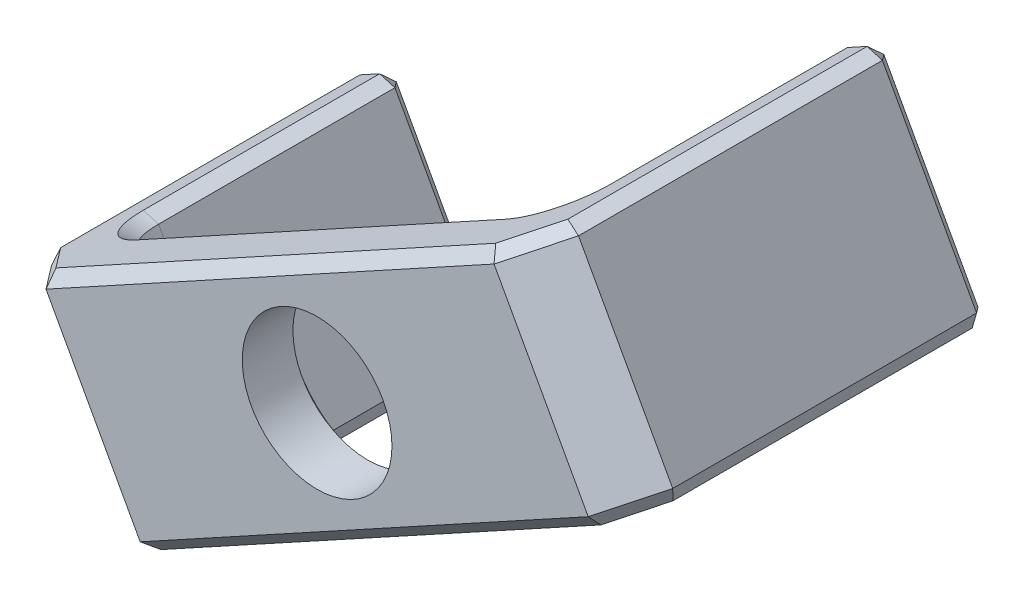
SolidWorks part; units mm, degrees
ref_plane "Front Plane" through (0, 0, 0) normal (0, 0, 1) x (1, 0, 0)
ref_plane "Top Plane" through (0, 0, 0) normal (0, 1, 0) x (1, 0, 0)
ref_plane "Right Plane" through (0, 0, 0) normal (1, 0, 0) x (0, 0, -1)
sketch "Sketch1" plane through (0, 0, 0) normal (0, 0, 1) x (1, 0, 0)
  line L8 (15.2366, 19.4223) -> (24.5673, 2.4136)
  line L10 (-15.2366, -19.4223) -> (-24.5673, -2.4136)
  line L12 (24.129, 2.1731) -> (-14.7982, -19.1818)
  line L14 (-24.129, -2.1731) -> (14.7982, 19.1818)
  line L16 (-14.7982, -19.1818) -> (-15.2366, -19.4223)
  line L17 (-24.129, -2.1731) -> (-24.5673, -2.4136)
  line L18 (14.7982, 19.1818) -> (15.2366, 19.4223)
  line L19 (24.129, 2.1731) -> (24.5673, 2.4136)
  circle A1 centre (0, 0) radius 6.65
extrude "Boss-Extrude1" add sketch "Sketch1" against normal blind 6
sketch "Sketch2" plane through (0, 0, 0) normal (0, 0, 1) x (1, 0, 0)
  line L0 (24.5673, 2.4136) -> (15.2366, 19.4223) construction
  line L1 (-24.5673, -2.4136) -> (-15.2366, -19.4223) construction
  line L2 (24.5673, 2.4136) -> (15.2366, 19.4223)
  line L3 (-24.5673, -2.4136) -> (-15.2366, -19.4223)
  line L4 (-15.2366, -19.4223) -> (-18.7435, -21.3462)
  line L5 (-18.7435, -21.3462) -> (-28.0743, -4.3375)
  line L6 (-28.0743, -4.3375) -> (-24.5673, -2.4136)
  line L7 (24.5673, 2.4136) -> (28.0743, 4.3375)
  line L8 (28.0743, 4.3375) -> (18.7435, 21.3462)
  line L9 (18.7435, 21.3462) -> (15.2366, 19.4223)
extrude "Boss-Extrude2" add sketch "Sketch2" against normal blind 32
fillet "Fillet1" radius 4 2 edges at (-19.902, -10.918, -6) (19.902, 10.918, -6)
chamfer "Chamfer1" distance 4 angle 45 2 edges at (-23.4089, -12.8418, 0) (23.4089, 12.8418, 0)
chamfer "Chamfer2" distance 1 angle 45 28 edges at (-23.4089, -12.8418, -32) (-19.902, -10.918, -32) (23.4089, 12.8418, -32) (-26.3208, -3.3755, -32) (-24.5673, -2.4136, -21) (-23.5402, -1.8501, -7.1716) (-4.6654, 8.5044, -6) (14.2094, 18.8588, -7.1716) (15.2366, 19.4223, -21) (-28.0743, -4.3375, -18) (-26.3208, -3.3755, -2) (-4.6654, 8.5044, 0) (16.9901, 20.3843, -2) (18.7435, 21.3462, -18) (16.9901, 20.3843, -32) (19.902, 10.918, -32) (26.3208, 3.3755, -2) (28.0743, 4.3375, -18) (26.3208, 3.3755, -32) (24.5673, 2.4136, -21) (23.5402, 1.8501, -7.1716) (4.6654, -8.5044, -6) (-14.2094, -18.8588, -7.1716) (-15.2366, -19.4223, -21) (-16.9901, -20.3843, -32) (-18.7435, -21.3462, -18) (-16.9901, -20.3843, -2) (4.6654, -8.5044, 0)
sketch "Sketch3" plane through (0, 0, -6) normal (0, 0, -1) x (-1, 0, 0)
  circle A0 centre (0, 0) radius 8.7
extrude "Cut-Extrude1" cut sketch "Sketch3" against normal blind 1.5
